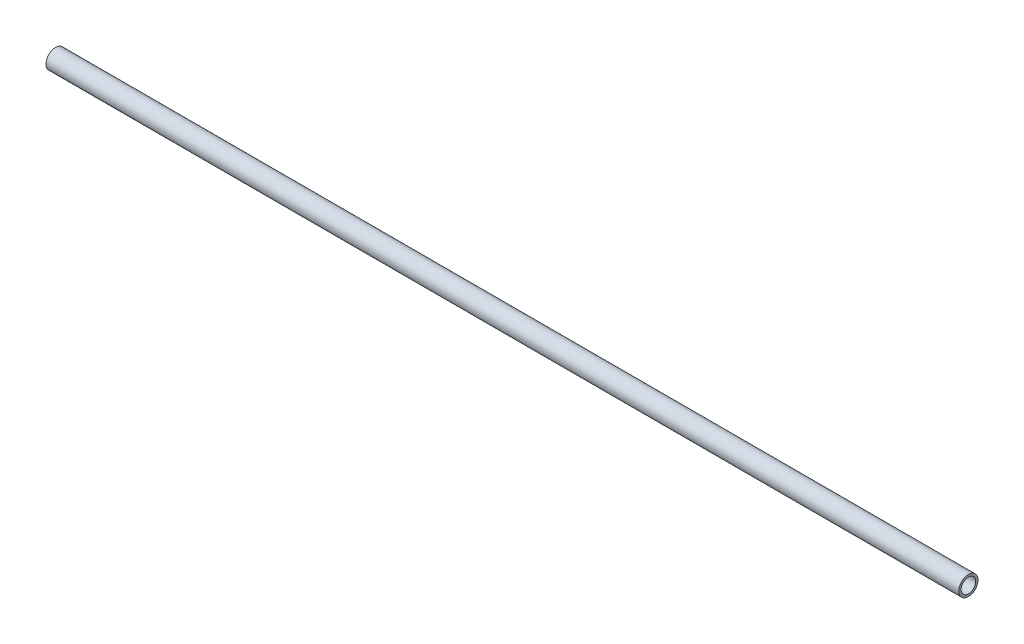
SolidWorks part; units mm, degrees
material "AISI 4130 Steel, annealed at 865C"
ref_plane "Front Plane" through (0, 0, 0) normal (0, 0, 1) x (1, 0, 0)
ref_plane "Top Plane" through (0, 0, 0) normal (0, 1, 0) x (1, 0, 0)
ref_plane "Right Plane" through (0, 0, 0) normal (1, 0, 0) x (0, 0, -1)
sketch "Sketch1" plane through (0, 0, 0) normal (1, 0, 0) x (0, 0, -1)
  circle A0 centre (0, 0) radius 12.7
  circle A1 centre (0, 0) radius 9.652
  dimension "D1" = 25.4
  dimension "D2" = 19.304
extrude "Boss-Extrude1" add sketch "Sketch1" along normal blind 1210
